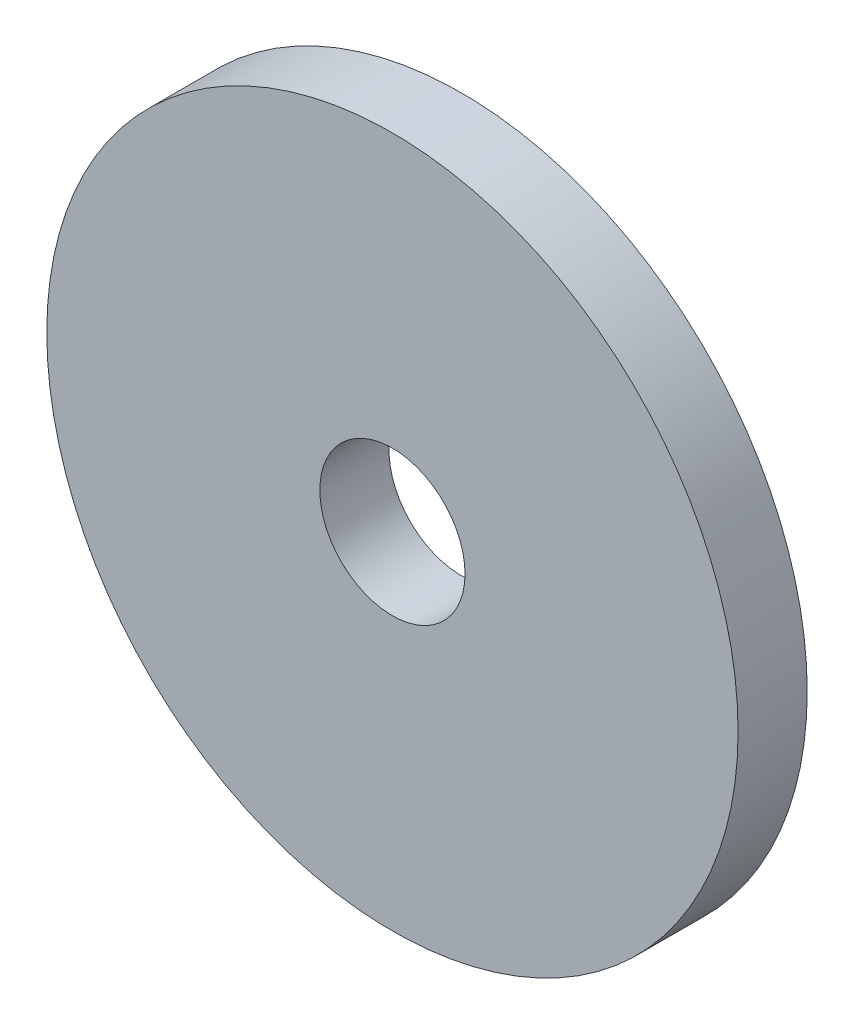
SolidWorks part; units mm, degrees
material "Plain Carbon Steel"
ref_plane "Спереди" through (0, 0, 0) normal (0, 0, 1) x (1, 0, 0)
ref_plane "Сверху" through (0, 0, 0) normal (0, 1, 0) x (1, 0, 0)
ref_plane "Справа" through (0, 0, 0) normal (1, 0, 0) x (0, 0, -1)
sketch "Sketch1" plane through (0, 0, 0) normal (0, 0, 1) x (1, 0, 0)
  circle A0 centre (0, 0) radius 25
  circle A1 centre (0, 0) radius 5.25
  dimension "D1" = 10.5
  dimension "D2" = 50
extrude "Extrude1" add sketch "Sketch1" along normal blind 5
